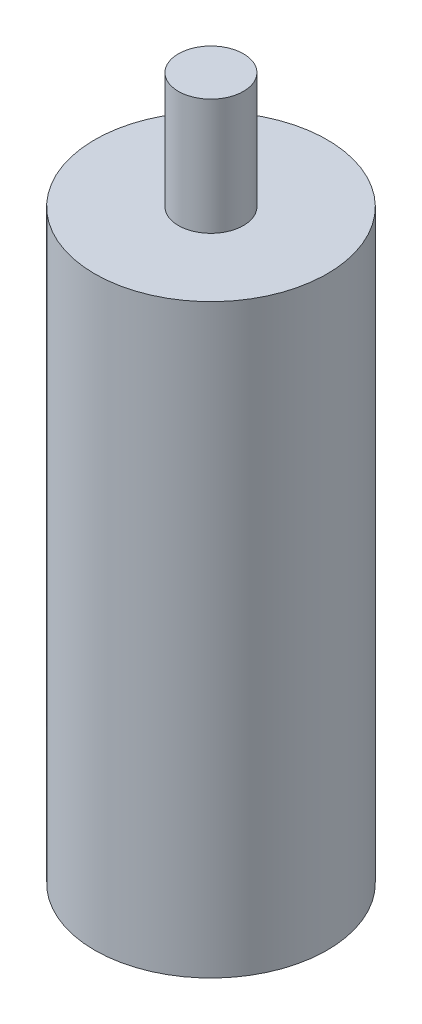
SolidWorks part; units mm, degrees
ref_plane "前视基准面" through (0, 0, 0) normal (0, 0, 1) x (1, 0, 0)
ref_plane "上视基准面" through (0, 0, 0) normal (0, 1, 0) x (1, 0, 0)
ref_plane "右视基准面" through (0, 0, 0) normal (1, 0, 0) x (0, 0, -1)
sketch "草图1" plane through (0, 0, 0) normal (0, 1, 0) x (1, 0, 0)
  circle A0 centre (0, 0) radius 12.5
  dimension "D1" = 25
extrude "凸台-拉伸1" add sketch "草图1" along normal blind 63
sketch "草图2" plane through (0, 63, 0) normal (0, 1, 0) x (1, 0, 0)
  circle A0 centre (0, 0) radius 3.5
  dimension "D1" = 7
extrude "凸台-拉伸2" add sketch "草图2" along normal blind 12.5
